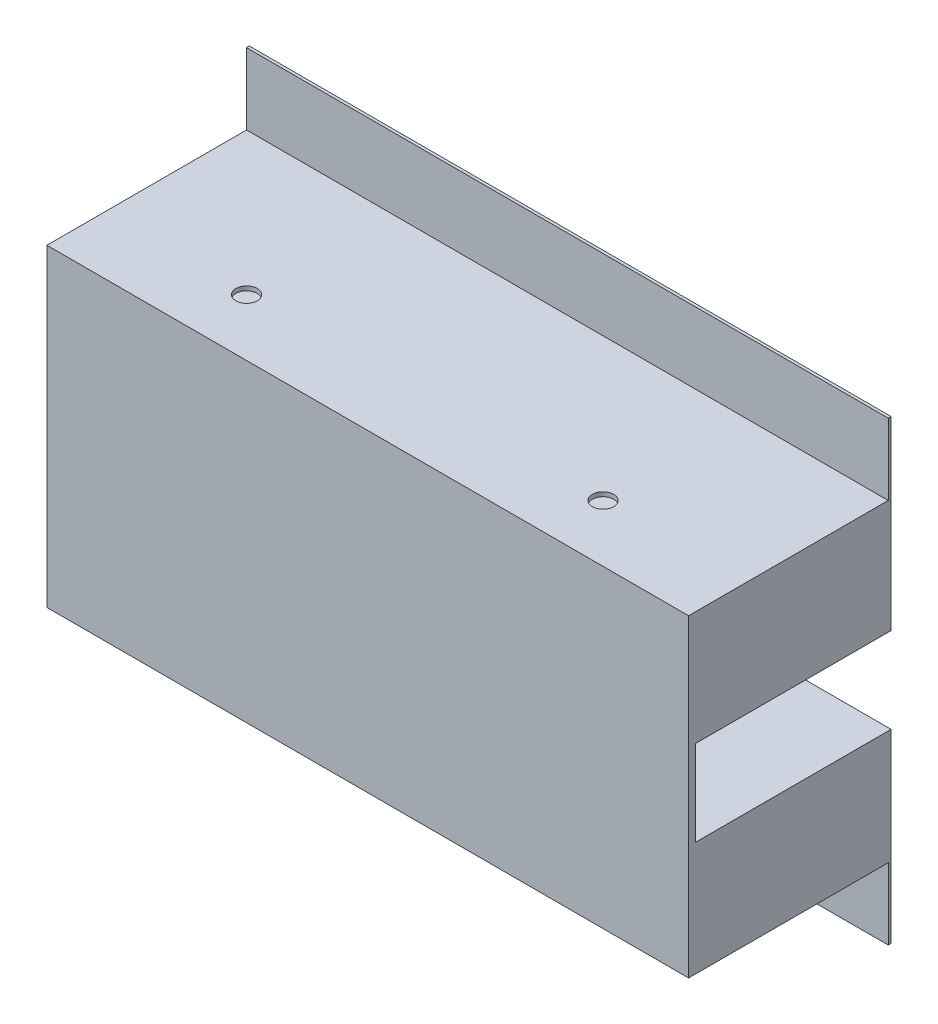
SolidWorks part; units mm, degrees
ref_plane "前视基准面" through (0, 0, 0) normal (0, 0, 1) x (1, 0, 0)
ref_plane "上视基准面" through (0, 0, 0) normal (0, 1, 0) x (1, 0, 0)
ref_plane "右视基准面" through (0, 0, 0) normal (1, 0, 0) x (0, 0, -1)
other "Configuration Table"
sketch "草图1" plane through (0, 0, 0) normal (0, 0, 1) x (1, 0, 0)
  line L1 (-225, 110) -> (225, 110)
  line L2 (-225, 110) -> (-225, -110)
  line L3 (-225, -110) -> (225, -110)
  line L4 (225, 110) -> (225, -110)
  line L5 (-225, 110) -> (225, -110) construction
  line L6 (-225, -110) -> (225, 110) construction
  point P0 (0, 0)
extrude "凸台-拉伸1" add sketch "草图1" along normal blind 140
sketch "草图2" plane through (0, 0, 0) normal (0, 0, -1) x (-1, 0, 0)
  line L1 (-225, 160) -> (225, 160)
  line L2 (-225, 160) -> (-225, -160)
  line L3 (-225, -160) -> (225, -160)
  line L4 (225, 160) -> (225, -160)
  line L5 (-225, 160) -> (225, -160) construction
  line L6 (-225, -160) -> (225, 160) construction
  point P0 (0, 0)
extrude "凸台-拉伸2" add sketch "草图2" along normal blind 2
sketch "草图3" plane through (0, 0, -2) normal (0, 0, -1) x (-1, 0, 0)
  line L1 (-222, 107) -> (222, 107)
  line L2 (-222, 107) -> (-222, -107)
  line L3 (-222, -107) -> (222, -107)
  line L4 (222, 107) -> (222, -107)
  line L5 (-222, 107) -> (222, -107) construction
  line L6 (-222, -107) -> (222, 107) construction
  point P0 (0, 0)
extrude "切除-拉伸1" cut sketch "草图3" against normal blind 139
sketch "草图4" plane through (0, 0, 137) normal (0, 0, -1) x (-1, 0, 0)
  line L0 (0, 30) -> (0, -30)
  line L1 (-222, -34) -> (222, -34)
  line L2 (-222, -34) -> (-222, -30)
  line L3 (222, -34) -> (222, -30)
  line L4 (-222, 34) -> (222, 34)
  line L5 (-222, -34) -> (222, 34) construction
  line L6 (222, -34) -> (-222, 34) construction
  line L7 (-222, 30) -> (-222, 34)
  line L8 (-222, 30) -> (222, 30)
  line L10 (-222, -30) -> (222, -30)
  line L12 (-222, 30) -> (222, -30) construction
  line L13 (-222, -30) -> (222, 30) construction
  line L14 (222, 30) -> (222, 34)
  point P0 (0, 0)
  point P4 (0, 0)
  point P6 (0, 0)
extrude "凸台-拉伸3" add sketch "草图4" along normal blind 139 contours L4 L14 L8 L7 | L10 L3 L1 L2
sketch "草图5" plane through (0, 0, -2) normal (0, 0, -1) x (-1, 0, 0)
  line L0 (-225, 0) -> (-125, 0) construction
  line L1 (-225, 160) -> (-225, -160) construction
  line L2 (-125, 77.0975) -> (-125, -77.0975) construction
  line L3 (-222, -34) -> (222, -34) construction
  line L4 (-155, 34) -> (-95, 34)
  line L5 (-155, 34) -> (-155, 30)
  line L6 (-155, -34) -> (-95, -34)
  line L7 (-95, 34) -> (-95, 30)
  line L8 (-155, 34) -> (-95, -34) construction
  line L9 (-155, -34) -> (-95, 34) construction
  line L10 (-222, -30) -> (222, -30) construction
  line L11 (-155, 30) -> (-95, 30)
  line L13 (-155, -30) -> (-95, -30)
  line L15 (-155, 30) -> (-95, -30) construction
  line L16 (-155, -30) -> (-95, 30) construction
  line L17 (-155, -30) -> (-155, -34)
  line L18 (-95, -30) -> (-95, -34)
  point P8 (-125, 0)
extrude "凸台-拉伸4" add sketch "草图5" along normal blind 30 contours L11 L5 L4 L7 | L13 L17 L6 L18
sketch "草图6" plane through (225, 0, 0) normal (1, 0, 0) x (0, 0, -1)
  line L0 (2, 30) -> (2, -30)
  line L1 (2, 30) -> (-135, 30)
  line L2 (2, -30) -> (-135, -30)
  line L3 (-135, 30) -> (-135, -30)
extrude "切除-拉伸2" cut sketch "草图6" against normal blind 10
sketch "草图7" plane through (0, -34, 0) normal (0, -1, 0) x (1, 0, 0)
  line L0 (95, -2) -> (155, -2) construction
  circle A0 centre (125, -2) radius 7.5
extrude "切除-拉伸3" cut sketch "草图7" against normal blind 70
sketch "草图8" plane through (0, 0, 137) normal (0, 0, -1) x (-1, 0, 0)
  line L0 (-222, 0) -> (13, 0) construction
  line L1 (-222, 30) -> (-222, -30) construction
  line L2 (13, -30) -> (13, 30)
  line L3 (13, -30) -> (11, -30)
  line L4 (13, 30) -> (11, 30)
  line L5 (11, -30) -> (11, 30)
  line L6 (-95, -30) -> (222, -30) construction
  line L7 (-95, 30) -> (222, 30) construction
extrude "凸台-拉伸5" add sketch "草图8" along normal blind 139
sketch "草图9" plane through (-225, 0, 0) normal (-1, 0, 0) x (0, 0, 1)
  line L0 (-2, 30) -> (-2, -30)
  line L1 (-2, 30) -> (28, 30)
  line L2 (-2, -30) -> (28, -30)
  line L3 (28, 30) -> (28, -30)
extrude "切除-拉伸4" cut sketch "草图9" against normal blind 240
sketch "草图10" plane through (0, -110, 0) normal (0, -1, 0) x (1, 0, 0)
  line L1 (225, 140) -> (125, 140) construction
  line L2 (225, 140) -> (225, 100) construction
  line L3 (225, 100) -> (125, 100) construction
  line L4 (125, 140) -> (125, 100) construction
  circle A0 centre (125, 100) radius 7.5
extrude "切除-拉伸5" cut sketch "草图10" against normal blind 220
sketch "草图11" plane through (0, -110, 0) normal (0, -1, 0) x (1, 0, 0)
  line L1 (-225, 140) -> (-125, 140) construction
  line L2 (-225, 140) -> (-225, 100) construction
  line L3 (-225, 100) -> (-125, 100) construction
  line L4 (-125, 140) -> (-125, 100) construction
  circle A0 centre (-125, 100) radius 7.5
extrude "切除-拉伸6" cut sketch "草图11" against normal blind 220
